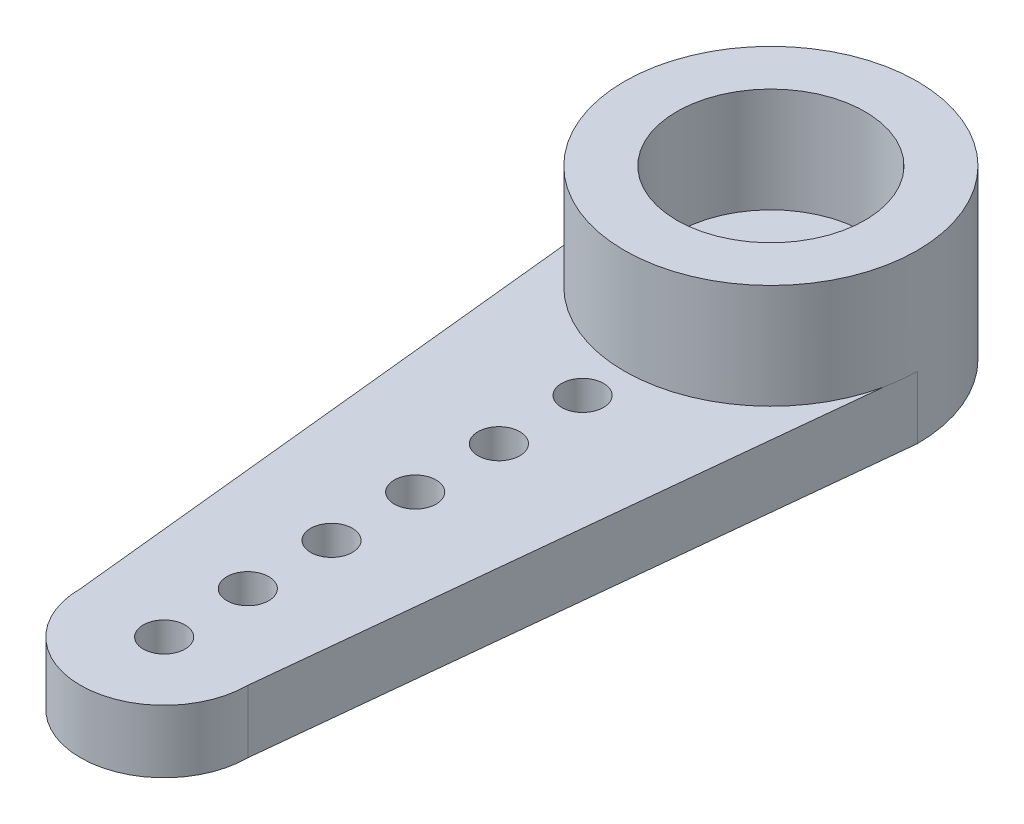
SolidWorks part; units mm, degrees
ref_plane "Alzado" through (0, 0, 0) normal (0, 0, 1) x (1, 0, 0)
ref_plane "Planta" through (0, 0, 0) normal (0, 1, 0) x (1, 0, 0)
ref_plane "Vista lateral" through (0, 0, 0) normal (1, 0, 0) x (0, 0, -1)
sketch "Croquis1" plane through (0, 0, 0) normal (0, 1, 0) x (1, 0, 0)
  line L0 (0, 0) -> (0, -10.5) construction
  line L2 (-3.5, 0) -> (-2, -14.5) construction
  line L3 (2, -14.5) -> (3.5, 0) construction
  line L4 (-3.5, 0) -> (-2, -14.5)
  line L5 (3.5, 0) -> (2, -14.5)
  arc A0 (3.5, 0) -> (-3.5, 0) centre (0, 0) ccw
  arc A1 (-2, -14.5) -> (2, -14.5) centre (0, -14.5) ccw
  circle A2 centre (0, -14.5) radius 0.5
  circle A3 centre (0, -12.5) radius 0.5
  circle A4 centre (0, -10.5) radius 0.5
  circle A5 centre (0, -8.5) radius 0.5
  circle A6 centre (0, -6.5) radius 0.5
  circle A7 centre (0, -4.5) radius 0.5
  dimension "D1" = 6
extrude "Saliente-Extruir1" add sketch "Croquis1" along normal blind 1.5
sketch "Croquis2" plane through (0, 1.5, 0) normal (0, 1, 0) x (1, 0, 0)
  circle A0 centre (0, 0) radius 2.25
  circle A1 centre (0, 0) radius 3.5
extrude "Saliente-Extruir2" add sketch "Croquis2" along normal blind 2.5
sketch "Croquis3" plane through (0, 0, 0) normal (0, -1, 0) x (1, 0, 0)
  circle A0 centre (0, 0) radius 2.5
extrude "Cortar-Extruir1" cut sketch "Croquis3" against normal blind 1
sketch "Croquis4" plane through (0, 1.5, 0) normal (0, 1, 0) x (1, 0, 0)
  circle A0 centre (0, 0) radius 1
extrude "Cortar-Extruir2" cut sketch "Croquis4" along direction (0, -1, 0) on the side against the normal blind 1
